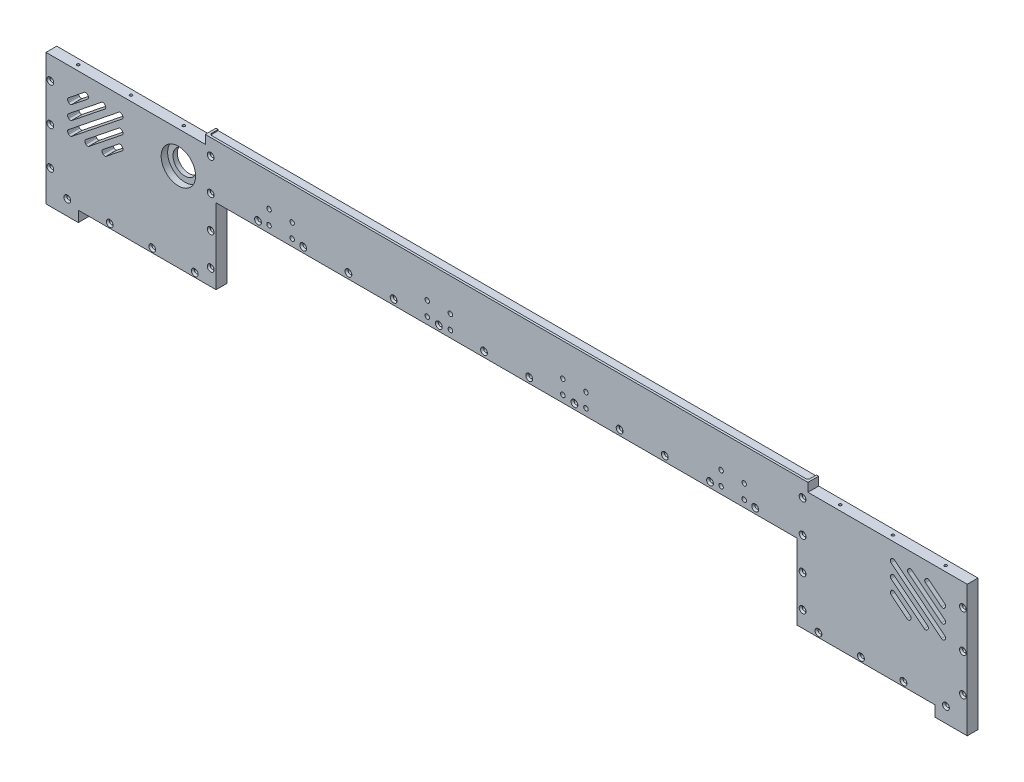
SolidWorks part; units mm, degrees
ref_plane "Front Plane" through (0, 0, 0) normal (0, 0, 1) x (1, 0, 0)
ref_plane "Top Plane" through (0, 0, 0) normal (0, 1, 0) x (1, 0, 0)
ref_plane "Right Plane" through (0, 0, 0) normal (1, 0, 0) x (0, 0, -1)
sketch "Sketch1" plane through (0, 0, 0) normal (0, 0, 1) x (1, 0, 0)
  line L0 (270, 0) -> (-270, 0)
  line L1 (-270, 0) -> (-270, -70)
  line L2 (-270, -70) -> (-398, -70)
  line L3 (-398, -70) -> (-398, -80)
  line L4 (-398, -80) -> (-428, -80)
  line L5 (-428, -80) -> (-428, 42)
  line L7 (0, 50) -> (0, 0) construction
  line L9 (398, -80) -> (428, -80)
  line L10 (398, -70) -> (398, -80)
  line L11 (270, -70) -> (398, -70)
  line L12 (270, 0) -> (270, -70)
  line L13 (-428, 42) -> (-280, 42)
  line L14 (-280, 42) -> (-280, 50)
  line L15 (-280, 50) -> (280, 50)
  line L16 (428, -80) -> (428, 42)
  line L17 (280, 42) -> (280, 50)
  line L18 (428, 42) -> (280, 42)
  point P17 (-280, 46)
  dimension "D1" = 540
  dimension "D2" = 42
  dimension "D3" = 70
  dimension "D4" = 10
  dimension "D5" = 158
  dimension "D6" = 30
  dimension "D7" = 50
  dimension "D8" = 10
extrude "Boss-Extrude1" add sketch "Sketch1" along normal blind 10
sketch "Sketch2" plane through (0, 42, 0) normal (0, 1, 0) x (1, 0, 0)
  point P0 (-305, -5)
  point P2 (-354, -5)
  point P4 (-403, -5)
hole_wizard "M3x0.5 Tapped Hole1" positions "3DSketch1" profile "Sketch4" tap size "M3x0.5" standard "BSI"
sketch3d "3DSketch1"
  point P0 (-403, 42, 5)
  point P3 (-354, 42, 5)
  point P6 (-305, 42, 5)
sketch "Sketch4" plane through (-403, 42, 5) normal (1, 0, 0) x (0, 0, 1)
  line L0 (0, 0) -> (0, 12.2511)
  line L1 (0, 12.2511) -> (1.25, 11.5)
  line L2 (1.25, 11.5) -> (1.25, 0)
  line L5 (1.25, 0) -> (0, 0)
  line L10 (0, 12.2511) -> (-1.25, 11.5) construction
  line L11 (0, -6.35) -> (0, 107.95) construction
  dimension "Tap Drill Dia." = 2.5
  dimension "Tap Drill Depth" = 11.5
  dimension "Drill Angle" = 118
cosmetic thread "Hole Thread1" parameters "D1"=10, "D2"=3.5
cosmetic thread "Hole Thread2" parameters "D1"=10, "D2"=3.5
cosmetic thread "Hole Thread3" parameters "D1"=10, "D2"=3.5
sketch "Sketch5" plane through (0, 0, 10) normal (0, 0, 1) x (1, 0, 0)
  line L0 (-270, -66) -> (-428, -66) construction
  line L1 (-270, -70) -> (-270, 0) construction
  line L2 (-428, 42) -> (-428, -80) construction
  line L3 (-398, -70) -> (-270, -70) construction
  line L4 (-349, -66) -> (-349, -70) construction
  point P8 (-408.25, -66)
  point P9 (-368.75, -66)
  point P12 (-329.25, -66)
  point P13 (-289.75, -66)
  dimension "D1" = 4
  dimension "D2" = 39.5
  dimension "D3" = 19.75
hole_wizard "CSK for M3 Countersunk Flat Head1" positions "3DSketch2" profile "Sketch6" countersink size "M3" standard "BSI"
sketch3d "3DSketch2"
  point P0 (-408.25, -66, 10)
  point P3 (-368.75, -66, 10)
  point P6 (-329.25, -66, 10)
  point P9 (-289.75, -66, 10)
sketch "Sketch6" plane through (-408.25, -66, 10) normal (1, 0, 0) x (0, -1, 0)
  line L0 (0, 0) -> (0, 12.5215)
  line L1 (0, 12.5215) -> (1.7, 11.5)
  line L2 (1.7, 11.5) -> (1.7, 1.45)
  line L3 (1.7, 1.45) -> (3.15, 0)
  line L5 (3.15, 0) -> (0, 0)
  line L6 (-1.7, 1.45) -> (-3.15, 0) construction
  line L10 (0, 12.5215) -> (-1.7, 11.5) construction
  line L11 (0, -6.35) -> (0, 107.95) construction
  dimension "Hole Dia." = 3.4
  dimension "Hole Depth" = 11.5
  dimension "Near C'Sink Dia." = 6.3
  dimension "Near C'Sink Angle" = 90
  dimension "Drill Angle" = 118
sketch "Sketch7" plane through (0, 0, 10) normal (0, 0, 1) x (1, 0, 0)
  line L0 (-424, 42) -> (-424, -70) construction
  line L1 (-280, 42) -> (-428, 42) construction
  line L2 (-424, -70) -> (-398, -70) construction
  line L3 (-428, 42) -> (-428, -80) construction
  point P8 (-424, -14)
  point P9 (-424, 21)
  point P10 (-424, -49)
  dimension "D1" = 4
  dimension "D2" = 35
  dimension "D3" = 35
hole_wizard "CSK for M3 Countersunk Flat Head2" positions "3DSketch3" profile "Sketch8" countersink size "M3" standard "BSI"
sketch3d "3DSketch3"
  point P0 (-424, 21, 10)
  point P3 (-424, -14, 10)
  point P6 (-424, -49, 10)
sketch "Sketch8" plane through (-424, 21, 10) normal (1, 0, 0) x (0, -1, 0)
  line L0 (0, 0) -> (0, 12.5215)
  line L1 (0, 12.5215) -> (1.7, 11.5)
  line L2 (1.7, 11.5) -> (1.7, 1.45)
  line L3 (1.7, 1.45) -> (3.15, 0)
  line L5 (3.15, 0) -> (0, 0)
  line L6 (-1.7, 1.45) -> (-3.15, 0) construction
  line L10 (0, 12.5215) -> (-1.7, 11.5) construction
  line L11 (0, -6.35) -> (0, 107.95) construction
  dimension "Hole Dia." = 3.4
  dimension "Hole Depth" = 11.5
  dimension "Near C'Sink Dia." = 6.3
  dimension "Near C'Sink Angle" = 90
  dimension "Drill Angle" = 118
sketch "Sketch10" plane through (0, 0, 10) normal (0, 0, 1) x (1, 0, 0)
  line L0 (-275, 50) -> (-275, -70) construction
  line L1 (280, 50) -> (-280, 50) construction
  line L2 (-398, -70) -> (-270, -70) construction
  line L3 (-270, -70) -> (-270, 0) construction
  line L5 (-275, -10) -> (-270, -10) construction
  point P8 (-275, 35)
  point P9 (-275, -25)
  point P11 (-275, -55)
  point P12 (-275, -10)
  point P13 (-275, 5)
  dimension "D1" = 5
  dimension "D2" = 15
  dimension "D3" = 30
hole_wizard "CSK for M3 Countersunk Flat Head3" positions "3DSketch4" profile "Sketch11" countersink size "M3" standard "BSI"
sketch3d "3DSketch4"
  point P0 (-275, 35, 10)
  point P3 (-275, 5, 10)
  point P6 (-275, -25, 10)
  point P9 (-275, -55, 10)
sketch "Sketch11" plane through (-275, 35, 10) normal (1, 0, 0) x (0, -1, 0)
  line L0 (0, 0) -> (0, 12.5215)
  line L1 (0, 12.5215) -> (1.7, 11.5)
  line L2 (1.7, 11.5) -> (1.7, 1.45)
  line L3 (1.7, 1.45) -> (3.15, 0)
  line L5 (3.15, 0) -> (0, 0)
  line L6 (-1.7, 1.45) -> (-3.15, 0) construction
  line L10 (0, 12.5215) -> (-1.7, 11.5) construction
  line L11 (0, -6.35) -> (0, 107.95) construction
  dimension "Hole Dia." = 3.4
  dimension "Hole Depth" = 11.5
  dimension "Near C'Sink Dia." = 6.3
  dimension "Near C'Sink Angle" = 90
  dimension "Drill Angle" = 118
sketch "Sketch12" plane through (0, 0, 10) normal (0, 0, 1) x (1, 0, 0)
  line L0 (-270, 5) -> (270, 5) construction
  line L1 (270, 0) -> (270, -70) construction
  line L2 (-270, -70) -> (-270, 0) construction
  line L3 (-270, 0) -> (270, 0) construction
  point P6 (-63, 5)
  point P7 (-105, 5)
  point P8 (-147, 5)
  point P9 (-189, 5)
  point P10 (-231, 5)
  point P11 (-21, 5)
  dimension "D1" = 21
  dimension "D2" = 42
  dimension "D3" = 42
  dimension "D4" = 42
  dimension "D5" = 42
  dimension "D6" = 42
  dimension "D7" = 5
hole_wizard "CSK for M3 Countersunk Flat Head4" positions "3DSketch5" profile "Sketch13" countersink size "M3" standard "BSI"
sketch3d "3DSketch5"
  point P0 (-231, 5, 10)
  point P3 (-189, 5, 10)
  point P6 (-147, 5, 10)
  point P9 (-105, 5, 10)
  point P12 (-63, 5, 10)
  point P15 (-21, 5, 10)
sketch "Sketch13" plane through (-231, 5, 10) normal (1, 0, 0) x (0, -1, 0)
  line L0 (0, 0) -> (0, 12.5215)
  line L1 (0, 12.5215) -> (1.7, 11.5)
  line L2 (1.7, 11.5) -> (1.7, 1.45)
  line L3 (1.7, 1.45) -> (3.15, 0)
  line L5 (3.15, 0) -> (0, 0)
  line L6 (-1.7, 1.45) -> (-3.15, 0) construction
  line L10 (0, 12.5215) -> (-1.7, 11.5) construction
  line L11 (0, -6.35) -> (0, 107.95) construction
  dimension "Hole Dia." = 3.4
  dimension "Hole Depth" = 11.5
  dimension "Near C'Sink Dia." = 6.3
  dimension "Near C'Sink Angle" = 90
  dimension "Drill Angle" = 118
mirror "Mirror1" about plane through (0, 0, 0) normal (1, 0, 0) of "M3x0.5 Tapped Hole1", "CSK for M3 Countersunk Flat Head1", "CSK for M3 Countersunk Flat Head2", "CSK for M3 Countersunk Flat Head3", "CSK for M3 Countersunk Flat Head4"
sketch "Sketch14" plane through (0, 50, 0) normal (0, 1, 0) x (1, 0, 0)
  line L5 (280, 0) -> (-280, 0) construction
  line L6 (-278, 0) -> (278, 0)
  line L7 (-278, 0) -> (-278, -8)
  line L8 (-278, -8) -> (278, -8)
  line L9 (278, 0) -> (278, -8)
  line L10 (280, -10) -> (280, 0) construction
  line L11 (280, -10) -> (-280, -10) construction
  line L12 (-280, -10) -> (-280, 0) construction
  dimension "D1" = 2
  dimension "D2" = 2
  dimension "D3" = 2
extrude "Cut-Extrude1" cut sketch "Sketch14" against normal blind 1
fillet "Fillet1" radius 2 2 edges at (-278, 49.5, 8) (278, 49.5, 8)
sketch "Sketch15" plane through (0, 0, 10) normal (0, 0, 1) x (1, 0, 0)
  line L0 (-270, -70) -> (-270, 0) construction
  line L2 (-280, 42) -> (-428, 42) construction
  circle A0 centre (-305, 12) radius 16
  dimension "D1" = 32
  dimension "D2" = 35
  dimension "D3" = 30
extrude "Cut-Extrude2" cut sketch "Sketch15" against normal blind 6
sketch "Sketch16" plane through (0, 0, 4) normal (0, 0, 1) x (1, 0, 0)
  circle A0 centre (-305, 12) radius 11
  circle A1 centre (-305, 12) radius 16 construction
  dimension "D1" = 22
extrude "Cut-Extrude3" cut sketch "Sketch16" against normal through all
sketch "Sketch17" plane through (0, 0, 10) normal (0, 0, 1) x (1, 0, 0)
  line L0 (-280, 50) -> (280, 50) construction
  line L1 (-227.85, 5) -> (-192.15, 5) construction
  line L2 (-73.75, 6.5) -> (-52.25, 6.5) construction
  line L3 (-52.25, 6.5) -> (-52.25, 19.5) construction
  line L6 (-63, 6.5) -> (-63, 0) construction
  line L9 (-270, 0) -> (270, 0) construction
  line L10 (-73.75, 6.5) -> (-73.75, 19.5) construction
  circle A0 centre (-231, 5) radius 3.15 construction
  circle A1 centre (-189, 5) radius 3.15 construction
  point P4 (0, 0)
  point P18 (-63, 6.5)
  point P25 (-210, 5)
  point P26 (-63, 5)
  dimension "D1" = 63
  dimension "D5" = 13
  dimension "D6" = 21.5
  dimension "D7" = 6.5
  dimension "D8" = 13
  dimension "D9" = 147
hole_wizard "M5x0.8 Tapped Hole1" positions "3DSketch6" profile "Sketch18" tap size "M5x0.8" standard "BSI" end condition through all
sketch3d "3DSketch6"
  point P0 (-52.25, 19.5, 10)
  point P3 (-73.75, 19.5, 10)
  point P6 (-73.75, 6.5, 10)
  point P9 (-52.25, 6.5, 10)
sketch "Sketch18" plane through (-52.25, 19.5, 10) normal (1, 0, 0) x (0, -1, 0)
  line L0 (0, 0) -> (0, 10)
  line L1 (0, 10) -> (2.1, 10)
  line L2 (2.1, 10) -> (2.1, 0)
  line L5 (2.1, 0) -> (0, 0)
  line L11 (0, -6.35) -> (0, 107.95) construction
  dimension "Thru Tap Drill Dia." = 4.2
  dimension "Thru Tap Drill Depth" = 10
cosmetic thread "Hole Thread4" parameters "D2"=5
cosmetic thread "Hole Thread5" parameters "D2"=5
cosmetic thread "Hole Thread6" parameters "D2"=5
cosmetic thread "Hole Thread7" parameters "D2"=5
pattern_linear "LPattern3" count 2 spacing 147 along (-1, 0, 0) of "M5x0.8 Tapped Hole1"
mirror "Mirror2" about plane through (0, 0, 0) normal (1, 0, 0) of "LPattern3", "M5x0.8 Tapped Hole1"
sketch "Sketch19" plane through (0, 0, 10) normal (0, 0, 1) x (1, 0, 0)
  line L0 (-357.2108, 27) -> (-407.2108, -13)
  line L1 (-407.2108, 27) -> (-357.2108, 27) construction
  line L2 (-407.2108, 27) -> (-407.2108, -13) construction
  line L3 (-407.2108, -13) -> (-357.2108, -13) construction
  line L4 (-357.2108, 27) -> (-357.2108, -13) construction
  line L5 (-280, 42) -> (-428, 42) construction
  line L6 (-373.2186, 27) -> (-407.2108, -0.1938)
  line L7 (-389.2264, 27) -> (-407.2108, 12.6125)
  line L8 (-391.2029, -13) -> (-357.2108, 14.1938)
  line L9 (-357.2108, 1.3875) -> (-375.1951, -13)
  dimension "D1" = 50
  dimension "D2" = 40
  dimension "D3" = 15
  dimension "D4" = 10
  dimension "D5" = 10
  dimension "D6" = 10
  dimension "D7" = 10
extrude "Cut-Extrude-Thin1" cut sketch "Sketch19" against normal blind 10 and the other way through all thin thin type mid plane wall 5
fillet "Fillet2" radius 2 20 edges at (-408.7725, 1.7584, 5) (-408.7725, -11.0478, 5) (-392.7647, -11.0478, 5) (-376.7569, -11.0478, 5) (-373.6334, -14.9522, 5) (-389.6412, -14.9522, 5) (-405.649, -14.9522, 5) (-405.649, -2.1459, 5) (-405.649, 10.6603, 5) (-408.7725, 14.5647, 5) (-355.649, -0.5647, 5) (-355.649, 12.2416, 5) (-355.649, 25.0478, 5) (-371.6568, 25.0478, 5) (-387.6646, 25.0478, 5) (-358.7725, 3.3397, 5) (-358.7725, 16.1459, 5) (-358.7725, 28.9522, 5) (-374.7803, 28.9522, 5) (-390.7881, 28.9522, 5)
mirror "Mirror3" about plane through (0, 0, 0) normal (1, 0, 0) of "Fillet2", "Cut-Extrude-Thin1"
equation "\"D3@Sketch5\"=\"D2@Sketch5\"/2"
equation "\"D6@Sketch12\"=\"D2@Sketch12\""
equation "\"D5@Sketch12\"=\"D2@Sketch12\""
equation "\"D4@Sketch12\"=\"D2@Sketch12\""
equation "\"D3@Sketch12\"=\"D2@Sketch12\""
equation "\"D1@Sketch12\"=\"D2@Sketch12\"/2"
equation "\"D2@Sketch10\"=\"D3@Sketch10\"/2"
